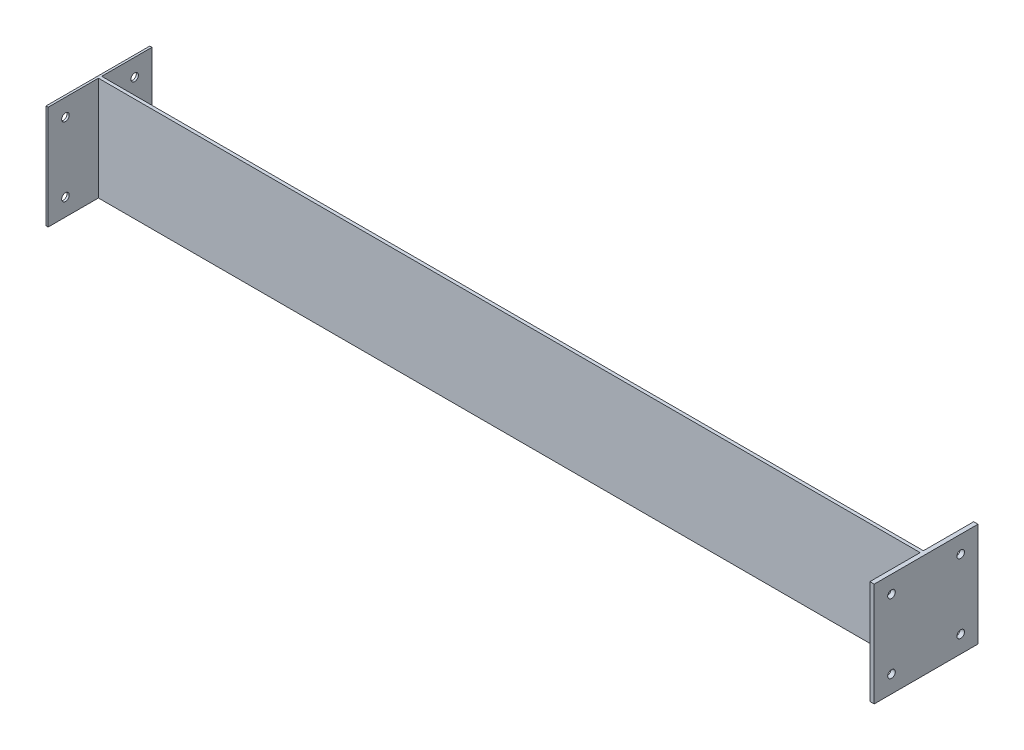
SolidWorks part; units mm, degrees
material "Galvanized Steel"
ref_plane "Front Plane" through (0, 0, 0) normal (0, 0, 1) x (1, 0, 0)
ref_plane "Top Plane" through (0, 0, 0) normal (0, 1, 0) x (1, 0, 0)
ref_plane "Right Plane" through (0, 0, 0) normal (1, 0, 0) x (0, 0, -1)
sketch "Sketch1" plane through (0, 0, 0) normal (1, 0, 0) x (0, 0, -1)
  line L1 (0, 0) -> (152.4, 0)
  line L2 (0, 0) -> (0, 152.4)
  line L3 (0, 152.4) -> (152.4, 152.4)
  line L4 (152.4, 0) -> (152.4, 152.4)
  dimension "D1" = 152.4
  dimension "D2" = 152.4
extrude "Boss-Extrude1" add sketch "Sketch1" along normal blind 3.175
sketch "Sketch2" plane through (3.175, 0, 0) normal (1, 0, 0) x (0, 0, -1)
  line L2 (152.4, 152.4) -> (0, 152.4) construction
  line L10 (73.8188, 152.4) -> (78.5813, 152.4)
  line L11 (73.8188, 152.4) -> (73.8188, 0)
  line L12 (73.8188, 0) -> (78.5813, 0)
  line L13 (78.5813, 152.4) -> (78.5813, 0)
  line L14 (0, 0) -> (152.4, 0) construction
  point P8 (76.2, 152.4)
  dimension "D2" = 4.7625
extrude "Boss-Extrude2" add sketch "Sketch2" along normal blind 1206.5
sketch "Sketch3" plane through (1209.675, 0, 0) normal (1, 0, 0) x (0, 0, -1)
  line L1 (0, 152.4) -> (152.4, 152.4)
  line L2 (0, 152.4) -> (0, 0)
  line L3 (0, 0) -> (152.4, 0)
  line L4 (152.4, 152.4) -> (152.4, 0)
extrude "Boss-Extrude3" add sketch "Sketch3" along normal blind 6.35
sketch "Sketch4" plane through (0, 0, 0) normal (-1, 0, 0) x (0, 0, 1)
  line L0 (-152.4, 0) -> (-152.4, 152.4) construction
  line L1 (-152.4, 152.4) -> (0, 152.4) construction
  line L2 (0, 0) -> (-152.4, 0) construction
  line L3 (0, 152.4) -> (0, 0) construction
  circle A0 centre (-127, 127) radius 5.5563
  circle A1 centre (-25.4, 127) radius 5.5562
  circle A2 centre (-25.4, 25.4) radius 5.5562
  circle A3 centre (-127, 25.4) radius 5.5563
  dimension "D1" = 11.1125
  dimension "D2" = 25.4
  dimension "D3" = 25.4
  dimension "D4" = 25.4
  dimension "D5" = 25.4
  dimension "D6" = 25.4
extrude "Cut-Extrude1" cut sketch "Sketch4" against normal blind 1219.2
